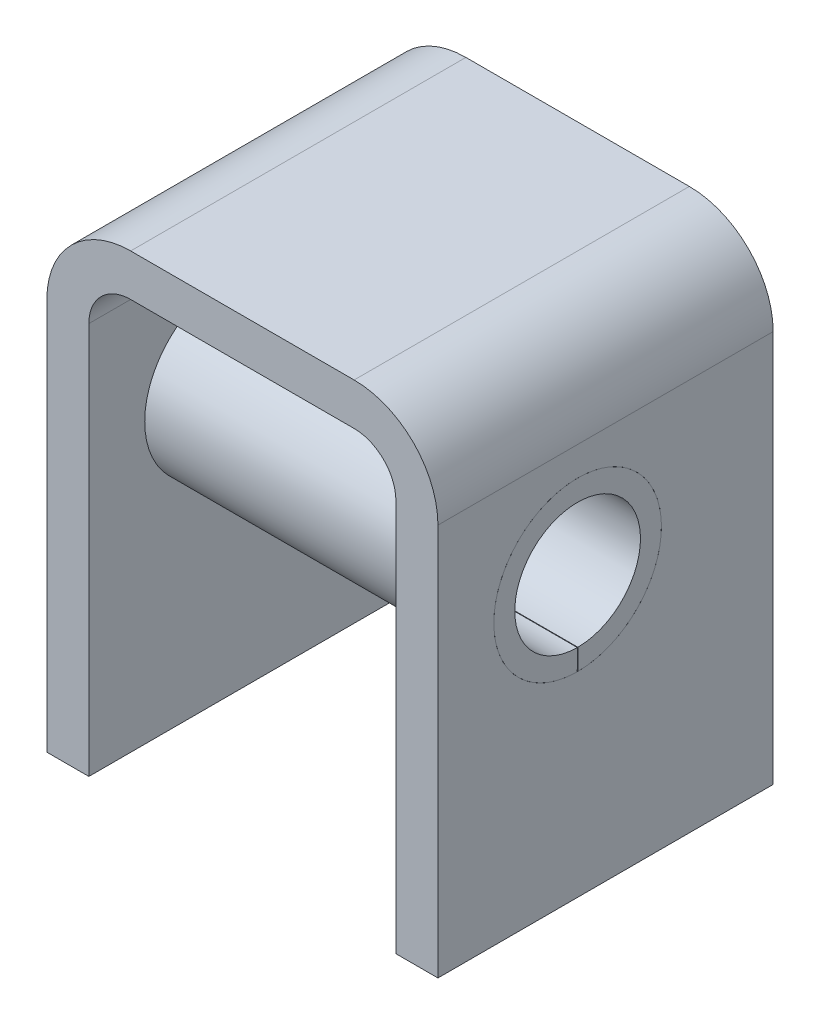
SolidWorks part; units mm, degrees
material "Plain Carbon Steel"
ref_plane "Front Plane" through (0, 0, 0) normal (0, 0, 1) x (1, 0, 0)
ref_plane "Top Plane" through (0, 0, 0) normal (0, 1, 0) x (1, 0, 0)
ref_plane "Right Plane" through (0, 0, 0) normal (1, 0, 0) x (0, 0, -1)
sketch "Sketch1" plane through (0, 0, 0) normal (0, 0, 1) x (1, 0, 0)
  line L0 (-17.4498, -9.525) -> (-17.4498, -54.102)
  line L1 (-12.7, 0) -> (12.7, 0)
  line L2 (-22.225, -9.525) -> (-22.225, -54.102)
  line L4 (22.225, -9.525) -> (22.225, -54.102)
  line L5 (-22.225, 0) -> (22.225, -54.102) construction
  line L6 (-22.225, -54.102) -> (22.225, 0) construction
  line L7 (-12.7, -4.7752) -> (12.7, -4.7752)
  line L8 (17.4498, -9.525) -> (17.4498, -54.102)
  line L9 (-22.225, -54.102) -> (-17.4498, -54.102)
  line L10 (17.4498, -54.102) -> (22.225, -54.102)
  line L11 (-22.225, -9.525) -> (-22.225, 0) construction
  line L12 (-22.225, 0) -> (-12.7, 0) construction
  line L13 (0, 0) -> (0, -4.7752) construction
  arc A0 (12.7, 0) -> (22.225, -9.525) centre (12.7, -9.525) cw
  arc A1 (-12.7, 0) -> (-22.225, -9.525) centre (-12.7, -9.525) ccw
  arc A2 (-12.7, -4.7752) -> (-17.4498, -9.525) centre (-12.7, -9.525) ccw
  arc A3 (12.7, -4.7752) -> (17.4498, -9.525) centre (12.7, -9.525) cw
  point P4 (0, -27.051)
  dimension "D3" = 9.525
  dimension "D1" = 54.102
  dimension "D2" = 44.45
  dimension "D4" = 22.225
  dimension "D6" = 34.8996
  dimension "D5" = 4.7752
extrude "Boss-Extrude1" add sketch "Sketch1" along normal mid plane 38.1
sketch "Sketch2" plane through (22.225, 0, 0) normal (1, 0, 0) x (0, 0, -1)
  line L0 (-3.175, 0) -> (-3.175, -22.352) construction
  line L1 (-19.05, 0) -> (19.05, 0) construction
  line L2 (-19.05, 0) -> (-19.05, -9.525) construction
  circle A0 centre (-3.175, -22.352) radius 9.525
  dimension "D1" = 19.05
  dimension "D2" = 22.352
  dimension "D3" = 15.875
extrude "Cut-Extrude1" cut sketch "Sketch2" against normal through all
sketch "Sketch3" plane through (0, 0, 0) normal (1, 0, 0) x (0, 0, -1)
  line L0 (-3.175, -29.4958) -> (-3.175, -31.877) construction
  line L1 (-3.175, -22.352) -> (-3.1438, -29.4957) construction
  line L2 (-3.1438, -29.4957) -> (-3.1334, -31.8769)
  line L3 (-3.2062, -29.4957) -> (-3.2166, -31.8769)
  circle A0 centre (-3.175, -22.352) radius 9.525 construction
  arc A1 (-3.1334, -31.8769) -> (-3.2166, -31.8769) centre (-3.175, -22.352) ccw
  arc A2 (-3.1438, -29.4957) -> (-3.2062, -29.4957) centre (-3.175, -22.352) ccw
  dimension "D1" = 14.2875
  dimension "D2" = 0.25
extrude "Boss-Extrude2" add sketch "Sketch3" along normal mid plane 44.45 separate body
